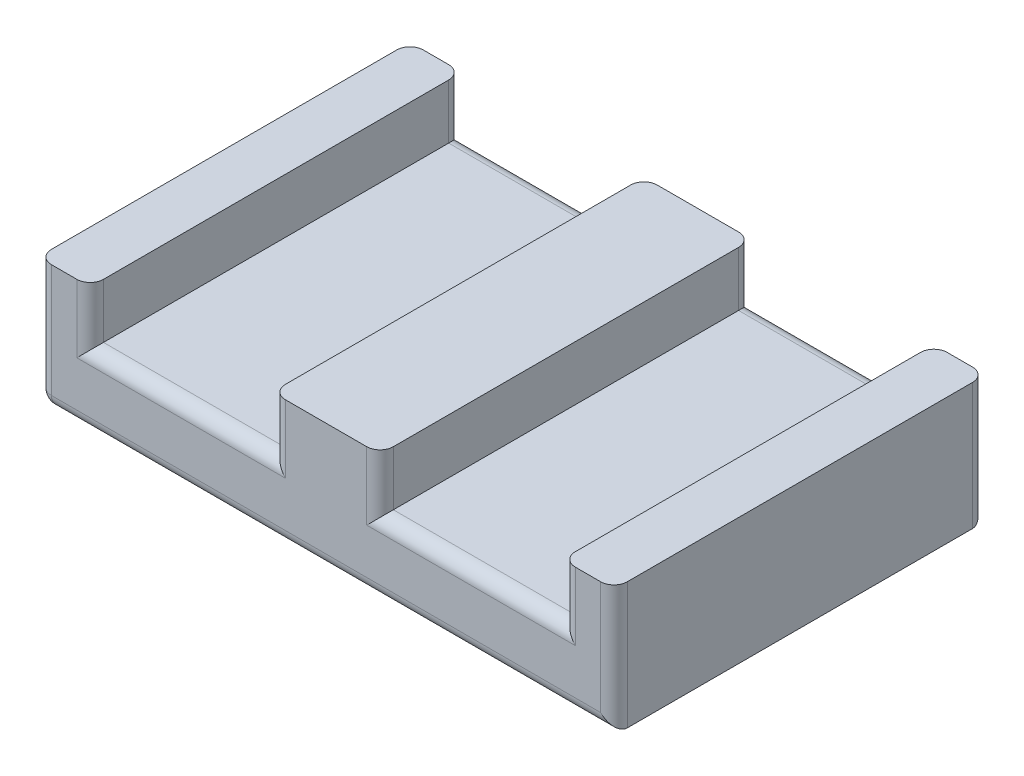
SolidWorks part; units mm, degrees
ref_plane "Спереди" through (0, 0, 0) normal (0, 0, 1) x (1, 0, 0)
ref_plane "Сверху" through (0, 0, 0) normal (0, 1, 0) x (1, 0, 0)
ref_plane "Справа" through (0, 0, 0) normal (1, 0, 0) x (0, 0, -1)
sketch "Эскиз1" plane through (0, 0, 0) normal (0, 1, 0) x (1, 0, 0)
  line L1 (-21.6, -13.95) -> (21.6, -13.95)
  line L2 (-21.6, -13.95) -> (-21.6, 13.95)
  line L3 (-21.6, 13.95) -> (21.6, 13.95)
  line L4 (21.6, -13.95) -> (21.6, 13.95)
  line L5 (-21.6, -13.95) -> (21.6, 13.95) construction
  line L6 (-21.6, 13.95) -> (21.6, -13.95) construction
  point P0 (0, 0)
extrude "Бобышка-Вытянуть1" add sketch "Эскиз1" along normal blind 5.4
sketch "Эскиз2" plane through (0, 5.4, 0) normal (0, 1, 0) x (1, 0, 0)
  line L0 (-21.6, -13.95) -> (21.6, -13.95) construction
  line L1 (-4.05, 13.95) -> (4.05, 13.95)
  line L2 (-4.05, 13.95) -> (-4.05, -13.95)
  line L3 (-4.05, -13.95) -> (4.05, -13.95)
  line L4 (4.05, 13.95) -> (4.05, -13.95)
  line L5 (-4.05, 13.95) -> (4.05, -13.95) construction
  line L6 (-4.05, -13.95) -> (4.05, 13.95) construction
  line L7 (21.6, 13.95) -> (-21.6, 13.95) construction
  line L8 (-21.6, -13.95) -> (-17.7, -13.95)
  line L9 (-21.6, -13.95) -> (-21.6, 13.95)
  line L10 (-21.6, 13.95) -> (-17.7, 13.95)
  line L11 (-17.7, -13.95) -> (-17.7, 13.95)
  line L13 (21.6, -13.95) -> (17.7, -13.95)
  line L14 (21.6, -13.95) -> (21.6, 13.95)
  line L15 (21.6, 13.95) -> (17.7, 13.95)
  line L16 (17.7, -13.95) -> (17.7, 13.95)
  point P0 (0, 0)
  dimension "D1" = 8.1
  dimension "D2" = 3.9
  dimension "D3" = 3.9
extrude "Бобышка-Вытянуть2" add sketch "Эскиз2" along normal blind 4.1
fillet "Скругление1" radius 1 19 edges at (10.875, 5.4, 13.95) (10.875, 5.4, -13.95) (-10.875, 5.4, -13.95) (-10.875, 5.4, 13.95) (0, 0, -13.95) (0, 0, 13.95) (21.6, 4.75, 13.95) (21.6, 4.75, -13.95) (17.7, 7.45, -13.95) (17.7, 7.45, 13.95) (4.05, 7.45, 13.95) (4.05, 7.45, -13.95) (-17.7, 7.45, 13.95) (-17.7, 7.45, -13.95) (-4.05, 7.45, -13.95) (-4.05, 7.45, 13.95) (-21.6, 4.75, -13.95) (-21.6, 4.75, 13.95) (-21.6, 0, 0)
